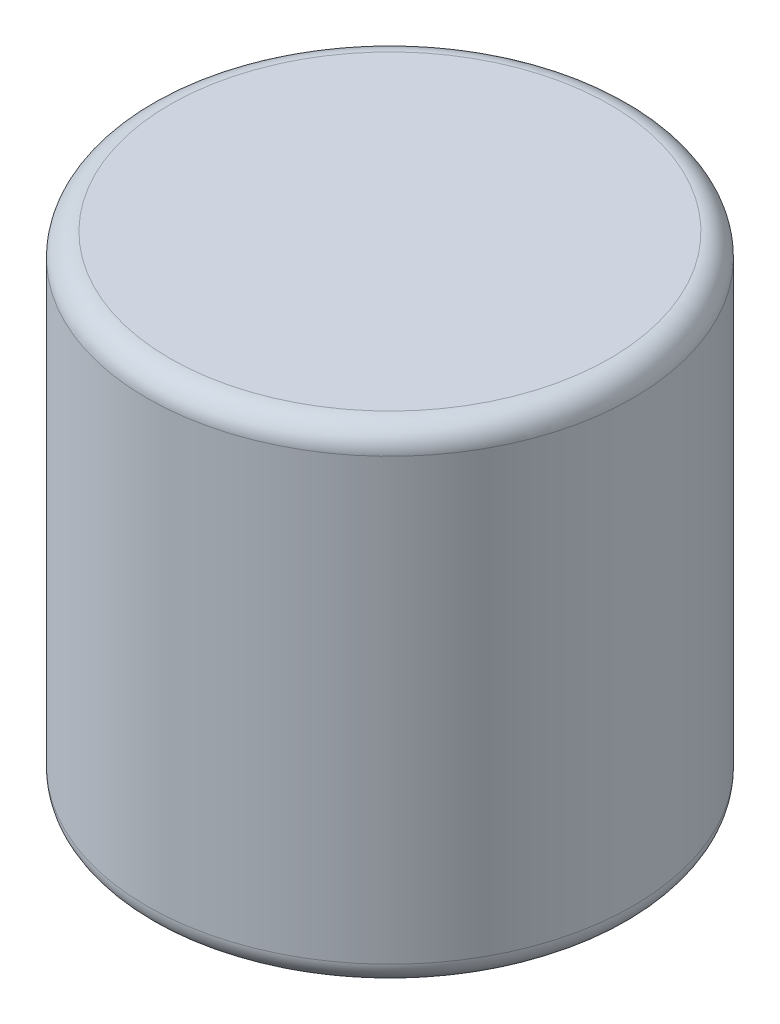
SolidWorks part; units mm, degrees
ref_plane "Front Plane" through (0, 0, 0) normal (0, 0, 1) x (1, 0, 0)
ref_plane "Top Plane" through (0, 0, 0) normal (0, 1, 0) x (1, 0, 0)
ref_plane "Right Plane" through (0, 0, 0) normal (1, 0, 0) x (0, 0, -1)
sketch "Sketch1" plane through (0, 0, 0) normal (0, 1, 0) x (1, 0, 0)
  circle A0 centre (0, 0) radius 3.175
  dimension "D1" = 6.35
extrude "Boss-Extrude1" add sketch "Sketch1" along normal blind 6.35
fillet "Fillet3" radius 0.3 2 edges at (0, 0, 3.175) (0, 6.35, 3.175)
